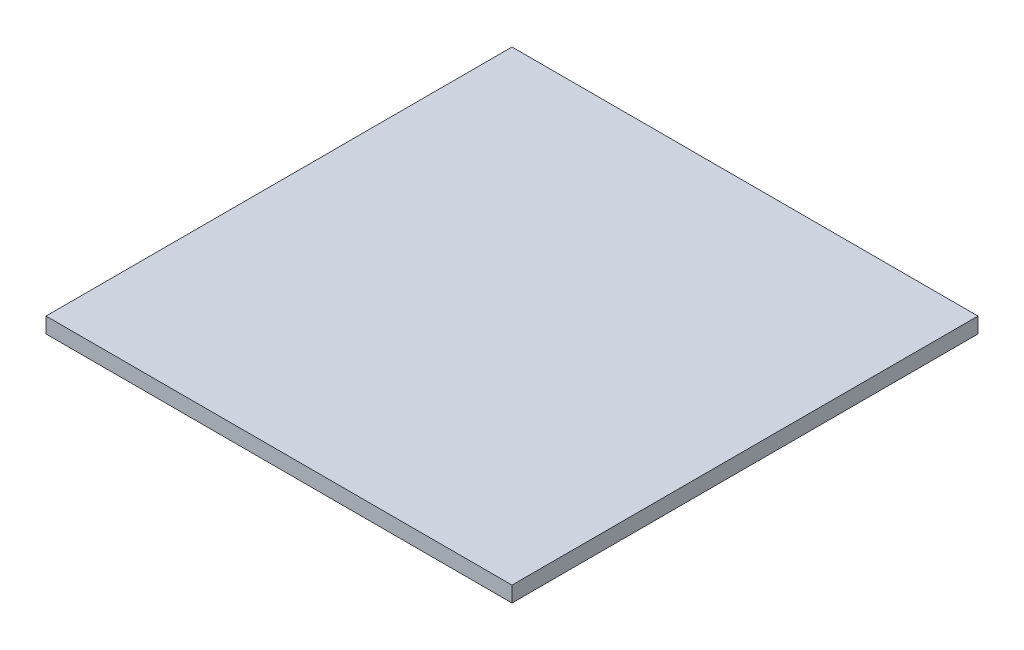
SolidWorks part; units mm, degrees
material "Ouro puro"
ref_plane "Plano frontal" through (0, 0, 0) normal (0, 0, 1) x (1, 0, 0)
ref_plane "Plano superior" through (0, 0, 0) normal (0, 1, 0) x (1, 0, 0)
ref_plane "Plano direito" through (0, 0, 0) normal (1, 0, 0) x (0, 0, -1)
sketch "Esboço1" plane through (0, 0, 0) normal (0, 1, 0) x (1, 0, 0)
  line L1 (0, 0) -> (300, 0)
  line L2 (0, 0) -> (0, 300)
  line L3 (0, 300) -> (300, 300)
  line L4 (300, 0) -> (300, 300)
  dimension "D1" = 300
  dimension "D2" = 300
extrude "Ressalto-extrusão1" add sketch "Esboço1" along normal blind 10
